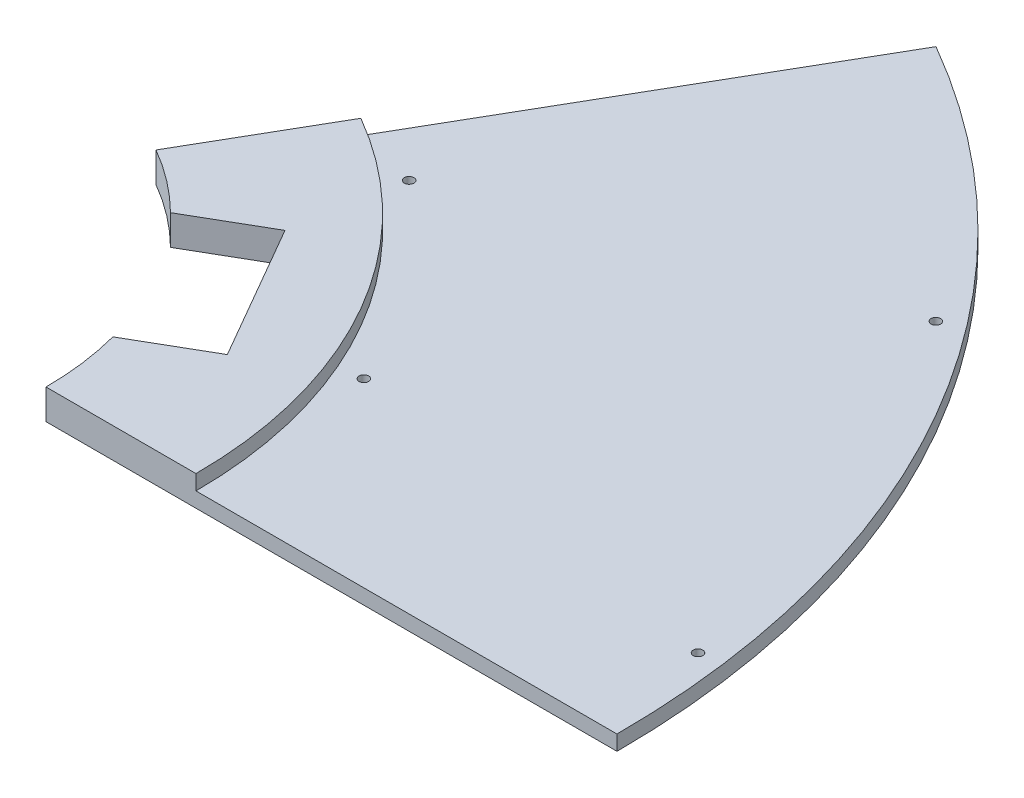
SolidWorks part; units mm, degrees
ref_plane "Ebene vorne" through (0, 0, 0) normal (0, 0, 1) x (1, 0, 0)
ref_plane "Ebene oben" through (0, 0, 0) normal (0, 1, 0) x (1, 0, 0)
ref_plane "Ebene rechts" through (0, 0, 0) normal (1, 0, 0) x (0, 0, -1)
sketch "Skizze1" plane through (0, 0, 0) normal (0, 1, 0) x (1, 0, 0)
  line L0 (0, 0) -> (290, 0)
  line L1 (0, 0) -> (145, 251.1474)
  arc A0 (290, 0) -> (145, 251.1474) centre (0, 0) ccw
  dimension "D1" = 290
  dimension "D2" = 60
extrude "Aufsatz-Linear austragen1" add sketch "Skizze1" along normal blind 5
sketch "Skizze2" plane through (0, 5, 0) normal (0, 1, 0) x (1, 0, 0)
  line L2 (145, 251.1474) -> (0, 0) construction
  line L3 (0, 0) -> (290, 0) construction
  line L4 (0, 0) -> (149.9, 0)
  line L5 (74.95, 129.8172) -> (0, 0)
  arc A0 (74.95, 129.8172) -> (149.9, 0) centre (0, 0) cw
  dimension "D1" = 149.9
extrude "Aufsatz-Linear austragen2" add sketch "Skizze2" along normal blind 5
sketch "Skizze3" plane through (0, 10, 0) normal (0, 1, 0) x (1, 0, 0)
  line L0 (0, 0) -> (129.8172, 74.95) construction
  line L2 (26.2, 45.3797) -> (94.6336, 84.8899)
  line L3 (74.95, 129.8172) -> (0, 0) construction
  line L4 (94.6336, 84.8899) -> (120.8336, 39.5101)
  line L5 (120.8336, 39.5101) -> (52.4, 0)
  line L6 (0, 0) -> (149.9, 0) construction
  line L7 (26.2, 45.3797) -> (0, 0)
  line L8 (0, 0) -> (52.4, 0)
  arc A0 (149.9, 0) -> (74.95, 129.8172) centre (0, 0) ccw construction
  point P10 (107.7336, 62.2)
  dimension "D1" = 52.4
  dimension "D2" = 124.4
extrude "Schnitt-Linear austragen1" cut sketch "Skizze3" against normal through all
sketch "Skizze4" plane through (0, 10, 0) normal (0, 1, 0) x (1, 0, 0)
  line L0 (74.95, 129.8172) -> (26.2, 45.3797) construction
  line L1 (52.4, 0) -> (149.9, 0) construction
  line L2 (100, 0) -> (0, 0)
  line L3 (0, 0) -> (50, 86.6025)
  arc A0 (50, 86.6025) -> (100, 0) centre (0, 0) cw
  dimension "D1" = 100
extrude "Schnitt-Linear austragen2" cut sketch "Skizze4" against normal through all
sketch "Skizze5" plane through (0, 5, 0) normal (0, 1, 0) x (1, 0, 0)
  line L0 (145, 251.1474) -> (74.95, 129.8172) construction
  line L1 (149.9, 0) -> (290, 0) construction
  line L2 (280.0832, 36.8736) -> (0, 0) construction
  line L3 (0, 0) -> (145.511, 60.2726) construction
  line L4 (224.1223, 171.9751) -> (0, 0) construction
  line L5 (0, 0) -> (95.8799, 124.9532) construction
  line L6 (100, 0) -> (149.9, 0) construction
  circle A0 centre (95.8799, 124.9532) radius 1.6
  circle A1 centre (224.1223, 171.9751) radius 1.6
  circle A2 centre (145.511, 60.2726) radius 1.6
  circle A3 centre (280.0832, 36.8736) radius 1.6
  arc A4 (78.75, 136.399) -> (157.5, 0) centre (0, 0) cw construction
  arc A5 (141.25, 244.6522) -> (282.5, 0) centre (0, 0) cw construction
  dimension "D1" = 3.2
  dimension "D2" = 157.5
  dimension "D3" = 282.5
  dimension "D4" = 7.5
  dimension "D5" = 22.5
  dimension "D6" = 30
  dimension "D7" = 30
extrude "Schnitt-Linear austragen3" cut sketch "Skizze5" against normal through all
chamfer "Fase1" distance 2 angle 45 4 edges at (280.0832, 0, -35.2736) (224.1223, 0, -170.3751) (95.8799, 0, -123.3532) (145.511, 0, -58.6726)
